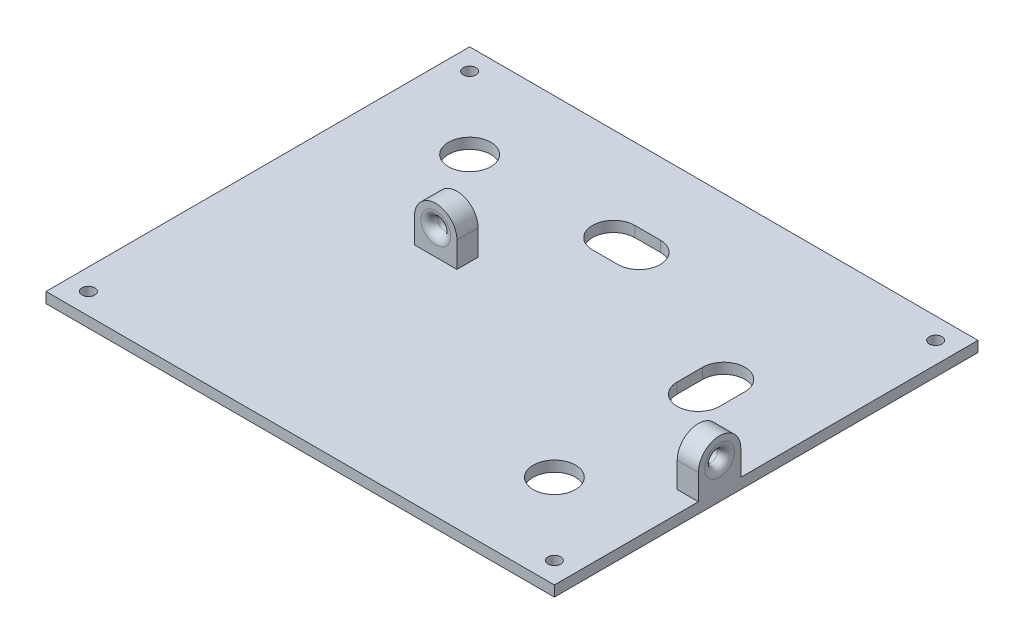
SolidWorks part; units mm, degrees
ref_plane "Front Plane" through (0, 0, 0) normal (0, 0, 1) x (1, 0, 0)
ref_plane "Top Plane" through (0, 0, 0) normal (0, 1, 0) x (1, 0, 0)
ref_plane "Right Plane" through (0, 0, 0) normal (1, 0, 0) x (0, 0, -1)
sketch "Sketch2" plane through (0, 0, 0) normal (0, 1, 0) x (1, 0, 0)
  line L1 (-60, 50) -> (60, 50)
  line L2 (-60, 50) -> (-60, -50)
  line L3 (-60, -50) -> (60, -50)
  line L4 (60, 50) -> (60, -50)
  line L5 (-60, 50) -> (60, -50) construction
  line L6 (-60, -50) -> (60, 50) construction
  point P0 (0, 0)
  dimension "D1" = 100
  dimension "D2" = 120
extrude "Boss-Extrude1" add sketch "Sketch2" along normal blind 2.5
sketch "Sketch3" plane through (0, 2.5, 0) normal (0, 1, 0) x (1, 0, 0)
  line L0 (60, -50) -> (60, 50) construction
  line L1 (-55, 45) -> (55, 45) construction
  line L2 (-55, 45) -> (-55, -45) construction
  line L3 (-55, -45) -> (55, -45) construction
  line L4 (55, 45) -> (55, -45) construction
  line L5 (-55, 45) -> (55, -45) construction
  line L6 (-55, -45) -> (55, 45) construction
  line L7 (-60, -50) -> (60, -50) construction
  circle A0 centre (-55, 45) radius 1.5
  circle A1 centre (55, 45) radius 1.5
  circle A2 centre (55, -45) radius 1.5
  circle A3 centre (-55, -45) radius 1.5
  point P0 (0, 0)
  dimension "D3" = 3
  dimension "D1" = 5
  dimension "D2" = 5
extrude "Cut-Extrude1" cut sketch "Sketch3" against normal blind 5
sketch "Sketch4" plane through (0, 2.5, 0) normal (0, 1, 0) x (1, 0, 0)
  line L0 (60, -50) -> (60, 50) construction
  line L1 (-60, -50) -> (60, -50) construction
  line L2 (60, 50) -> (-60, 50) construction
  line L4 (-60, 50) -> (-60, -50) construction
  circle A0 centre (-38, 28) radius 9.5 construction
  circle A1 centre (-4, 28) radius 9.5 construction
  circle A2 centre (38, 6) radius 9.5 construction
  circle A3 centre (38, -28) radius 9.5 construction
  circle A4 centre (-38, 28) radius 17 construction
  circle A5 centre (38, -28) radius 17 construction
  circle A6 centre (-38, 37.5) radius 1.65 construction
  circle A7 centre (-4, 37.5) radius 1.65 construction
  circle A8 centre (38, 15.5) radius 1.65 construction
  circle A9 centre (38, -18.5) radius 1.65 construction
  circle A10 centre (-28.5, 28) radius 1.65 construction
  circle A11 centre (-38, 18.5) radius 1.65 construction
  circle A12 centre (-47.5, 28) radius 1.65 construction
  circle A13 centre (5.5, 28) radius 1.65 construction
  circle A14 centre (-4, 18.5) radius 1.65 construction
  circle A15 centre (-13.5, 28) radius 1.65 construction
  circle A16 centre (47.5, 6) radius 1.65 construction
  circle A17 centre (38, -3.5) radius 1.65 construction
  circle A18 centre (28.5, 6) radius 1.65 construction
  circle A19 centre (47.5, -28) radius 1.65 construction
  circle A20 centre (38, -37.5) radius 1.65 construction
  circle A21 centre (28.5, -28) radius 1.65 construction
  circle A22 centre (-38, 28) radius 5
  circle A23 centre (-4, 28) radius 5
  circle A24 centre (38, 6) radius 5
  circle A25 centre (38, -28) radius 5
  dimension "D1" = 19
  dimension "D4" = 34
  dimension "D6" = 22
  dimension "D9" = 3.3
  dimension "D14" = 10
  dimension "D2" = 34
  dimension "D3" = 34
  dimension "D5" = 22
  dimension "D7" = 22
  dimension "D8" = 22
  dimension "D10" = 4
  dimension "D11" = 4
  dimension "D12" = 4
  dimension "D13" = 4
extrude "Cut-Extrude2" cut sketch "Sketch4" against normal blind 5
sketch "Sketch5" plane through (0, 2.5, 0) normal (0, 1, 0) x (1, 0, 0)
  line L0 (-4, 28) -> (2, 28) construction
  line L1 (-4, 33) -> (2, 33)
  line L2 (-4, 23) -> (2, 23)
  line L3 (38, 6) -> (38, 12) construction
  line L4 (33, 6) -> (33, 12)
  line L5 (43, 6) -> (43, 12)
  arc A0 (-4, 33) -> (-4, 23) centre (-4, 28) ccw
  arc A1 (2, 23) -> (2, 33) centre (2, 28) ccw
  arc A2 (33, 6) -> (43, 6) centre (38, 6) ccw
  arc A3 (43, 12) -> (33, 12) centre (38, 12) ccw
  circle A4 centre (38, 6) radius 5 construction
  point P3 (-1, 28)
  point P8 (38, 9)
  dimension "D1" = 6
extrude "Cut-Extrude3" cut sketch "Sketch5" against normal blind 10
sketch "Sketch6" plane through (0, 2.5, 0) normal (0, 1, 0) x (1, 0, 0)
  line L0 (-38, 28) -> (-4, 28) construction
  line L1 (38, -11) -> (55, -11) construction
  line L2 (38, 6) -> (38, -28) construction
  line L3 (-26, 8) -> (-16, 8)
  line L4 (60, -50) -> (60, 50) construction
  line L5 (55, -16) -> (60, -16)
  line L6 (55, -16) -> (55, -6)
  line L7 (55, -6) -> (60, -6)
  line L8 (60, -16) -> (60, -6)
  line L9 (-26, 50) -> (-16, 50)
  line L10 (-26, 50) -> (-26, 45)
  line L11 (-26, 45) -> (-16, 45)
  line L12 (-16, 50) -> (-16, 45)
  line L13 (60, 50) -> (-60, 50) construction
  line L14 (-26, 8) -> (-26, 3)
  line L15 (-26, 3) -> (-16, 3)
  line L16 (-16, 8) -> (-16, 3)
  line L17 (13, -6) -> (18, -6)
  line L18 (13, -6) -> (13, -16)
  line L19 (13, -16) -> (18, -16)
  line L20 (18, -6) -> (18, -16)
  line L21 (-21, 28) -> (-21, 45) construction
  dimension "D1" = 0
  dimension "D2" = 5
  dimension "D3" = 10
  dimension "D4" = 10
  dimension "D5" = 5
  dimension "D6" = 0
  dimension "D7" = 20
  dimension "D8" = 20
extrude "Boss-Extrude2" add sketch "Sketch6" along normal blind 15
sketch "Sketch7" plane through (0, 0, -3) normal (0, 0, 1) x (1, 0, 0)
  line L0 (-26, 17.5) -> (-16, 17.5) construction
  line L1 (-60, 2.5) -> (60, 2.5) construction
  line L2 (-26, 17.5) -> (-26, 2.5) construction
  line L3 (-16, 17.5) -> (-16, 2.5) construction
  line L8 (-26, 2.5) -> (-16, 2.5)
  line L9 (-16, 2.5) -> (-16, 17.5)
  line L10 (-16, 17.5) -> (-26, 17.5)
  line L11 (-26, 17.5) -> (-26, 2.5)
  line L13 (-16, 8.5) -> (-16, 17.5)
  line L14 (-16, 17.5) -> (-26, 17.5)
  line L15 (-26, 17.5) -> (-26, 8.5)
  circle A0 centre (-21, 8.5) radius 1.5
  arc A1 (-26, 8.5) -> (-16, 8.5) centre (-21, 8.5) cw
  point P4 (-21, 17.5)
  dimension "D1" = 3
  dimension "D2" = 6
  dimension "D3" = 0
sketch "Sketch8" plane through (13, 0, -13) normal (-1, 0, 0) x (0, 0, 1)
  line L4 (-37, 2.5) -> (63, 2.5) construction
  line L13 (29, 8.5) -> (29, 17.5)
  line L14 (29, 17.5) -> (19, 17.5)
  line L15 (19, 17.5) -> (19, 8.5)
  circle A0 centre (24, 8.5) radius 1.5
  arc A1 (19, 8.5) -> (29, 8.5) centre (24, 8.5) cw
  dimension "D1" = 3
  dimension "D2" = 6
extrude "Cut-Extrude4" cut sketch "Sketch7" against normal through all
extrude "Cut-Extrude5" cut sketch "Sketch8" against normal through all
fillet "Fillet1" radius 2 8 edges at (55, 8.5, 9.5) (60, 8.5, 12.5) (18, 8.5, 12.5) (-19.5, 8.5, -8) (-19.5, 8.5, -50) (-22.5, 8.5, -45) (13, 8.5, 12.5) (-19.5, 8.5, -3)
sketch "Sketch9" plane through (0, 2.5, 0) normal (0, 1, 0) x (1, 0, 0)
  line L1 (-26, 50) -> (-16, 50)
  line L2 (-26, 50) -> (-26, 45)
  line L3 (-26, 45) -> (-16, 45)
  line L4 (-16, 50) -> (-16, 45)
  line L5 (13, -16) -> (18, -16)
  line L6 (13, -16) -> (13, -6)
  line L7 (13, -6) -> (18, -6)
  line L8 (18, -16) -> (18, -6)
extrude "Cut-Extrude6" cut sketch "Sketch9" along normal blind 15
